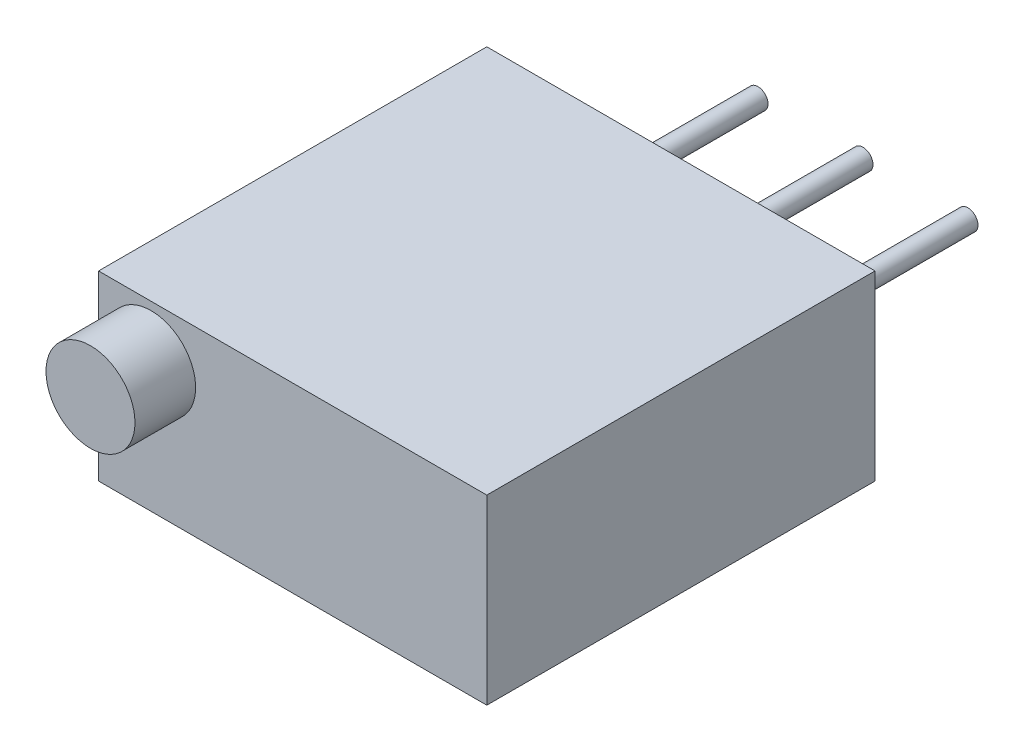
SolidWorks part; units mm, degrees
ref_plane "前视" through (0, 0, 0) normal (0, 0, 1) x (1, 0, 0)
ref_plane "上视" through (0, 0, 0) normal (0, 1, 0) x (1, 0, 0)
ref_plane "右视" through (0, 0, 0) normal (1, 0, 0) x (0, 0, -1)
sketch "草图1" plane through (0, 0, 0) normal (0, 1, 0) x (1, 0, 0)
  line L0 (0, 81.3418) -> (0, -101.3275) construction
  line L1 (-87.3375, 0) -> (113.7186, 0) construction
  line L3 (-4.8, 4.8) -> (4.8, 4.8)
  line L4 (-4.8, 4.8) -> (-4.8, -4.8)
  line L5 (-4.8, -4.8) -> (4.8, -4.8)
  line L6 (4.8, 4.8) -> (4.8, -4.8)
  dimension "D1" = 9.6
  dimension "D2" = 9.6
extrude "拉伸1" add sketch "草图1" along normal blind 4.5
sketch "草图3" plane through (0, 0, -4.8) normal (0, 0, -1) x (-1, 0, 0)
  line L0 (-5.1663, 2.25) -> (6.6013, 2.25) construction
  line L2 (0, 5.9307) -> (0, -2.165) construction
  circle A0 centre (0, 2.25) radius 0.25
  circle A1 centre (2.596, 2.25) radius 0.25
  circle A2 centre (-2.596, 2.25) radius 0.25
  dimension "D1" = 0.5
extrude "拉伸3" add sketch "草图3" along normal blind 4.5
sketch "草图4" plane through (0, 0, 4.8) normal (0, 0, 1) x (1, 0, 0)
  line L0 (-4.8, 3.2) -> (-3.5, 3.2)
  line L1 (-4.8, 4.5) -> (-4.8, 0) construction
  circle A0 centre (-3.5, 3.2) radius 1.1
  dimension "D3" = 2.2
  dimension "D1" = 1.3
  dimension "D2" = 1.3
extrude "凸台-拉伸1" add sketch "草图4" along normal blind 1.5
